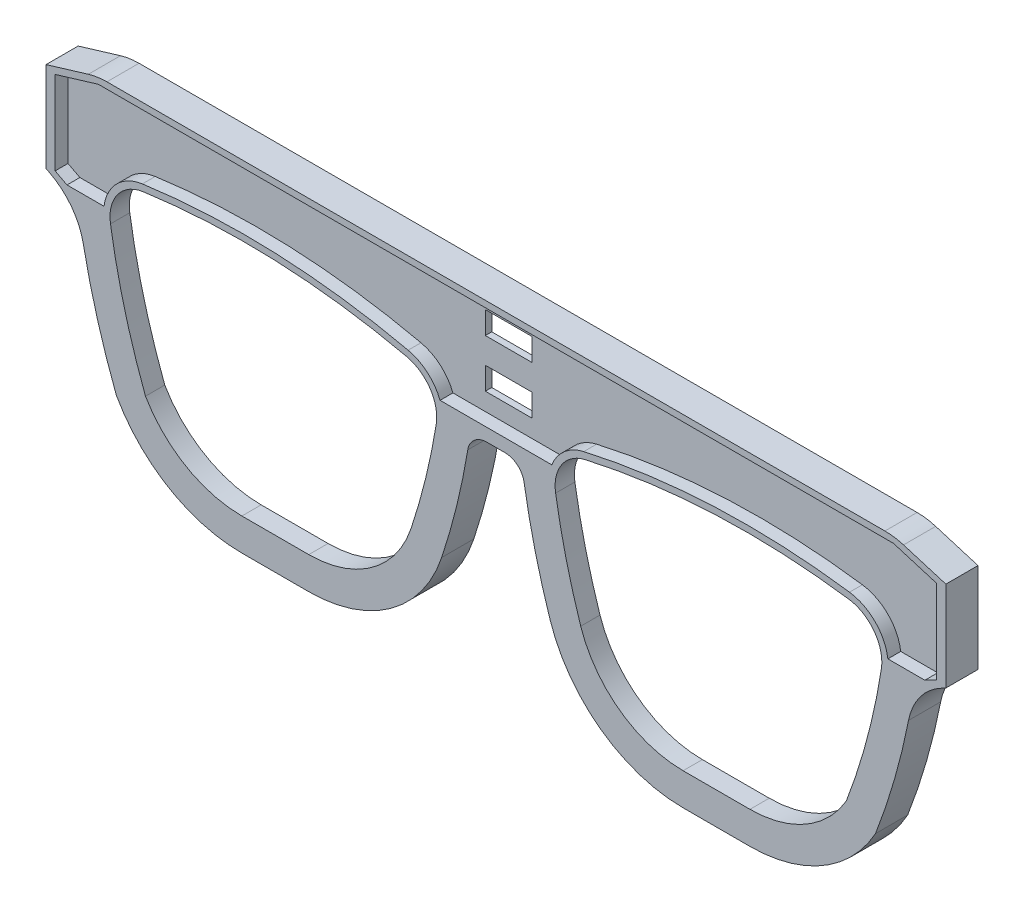
SolidWorks part; units mm, degrees
ref_plane "Front Plane" through (0, 0, 0) normal (0, 0, 1) x (1, 0, 0)
ref_plane "Top Plane" through (0, 0, 0) normal (0, 1, 0) x (1, 0, 0)
ref_plane "Right Plane" through (0, 0, 0) normal (1, 0, 0) x (0, 0, -1)
sketch "Sketch1" plane through (0, 0, 0) normal (0, 0, 1) x (1, 0, 0)
  line L4 (-70, 16.5826) -> (-70, 2.5826)
  line L5 (-70, 2.5826) -> (-65, -0.0353)
  line L6 (-39.5244, -34) -> (-29.1194, -34)
  line L7 (-4, 0) -> (0, 0)
  line L8 (0, 45.3197) -> (0, -37.9766) construction
  line L11 (-62, 19) -> (0, 19)
  line L12 (0, 19) -> (0, 0)
  line L13 (-70, 16.5826) -> (-62, 19)
  arc A2 (-8.4439, -19.0581) -> (-4, 0) centre (-111.6609, 15.057) ccw
  arc A3 (-65, -0.0353) -> (-59.0574, -22.499) centre (40.965, 15.9791) ccw
  arc A4 (-59.0574, -22.499) -> (-39.5244, -34) centre (-39.5244, -11.6623) ccw
  arc A5 (-29.1194, -34) -> (-8.4439, -19.0581) centre (-29.1194, -12.2244) ccw
  dimension "D8" = 5
  dimension "D1" = 4
  dimension "D2" = 53
  dimension "D3" = 34
  dimension "D4" = 70
  dimension "D5" = 8
  dimension "D7" = 14
extrude "Boss-Extrude1" add sketch "Sketch1" along normal blind 5 contours L4 L5 A3 A4 L6 A5 A2 L7 L12 L11 L13
sketch "Sketch2" plane through (0, 0, 5) normal (0, 0, 1) x (1, 0, 0)
  line L7 (-39.5244, -29) -> (-29.1194, -29)
  line L8 (-39.5244, -29) -> (-29.1194, -29)
  arc A15 (-60.0561, 0.7118) -> (-59.2887, 6.3037) centre (-50.178, 2.2047) cw
  arc A16 (-59.2887, 6.3037) -> (-8.9375, 4.059) centre (-39.064, -105.8745) cw
  arc A17 (-8.9375, 4.059) -> (-8.9518, 0.6925) centre (-21.3647, 2.4286) cw
  arc A19 (-13.1913, -17.489) -> (-8.9518, 0.6925) centre (-111.6609, 15.057) ccw
  arc A20 (-29.1194, -29) -> (-13.1913, -17.489) centre (-29.1194, -12.2244) ccw
  arc A21 (-54.5219, -20.3612) -> (-39.5244, -29) centre (-39.5244, -11.6623) ccw
  arc A22 (-60.0561, 0.7118) -> (-54.5219, -20.3612) centre (40.965, 15.9791) ccw
  arc A23 (-13.1913, -17.489) -> (-8.9518, 0.6925) centre (-111.6609, 15.057) ccw
  arc A24 (-29.1194, -29) -> (-13.1913, -17.489) centre (-29.1194, -12.2244) ccw
  arc A25 (-54.5219, -20.3612) -> (-39.5244, -29) centre (-39.5244, -11.6623) ccw
  arc A26 (-60.0561, 0.7118) -> (-54.5219, -20.3612) centre (40.965, 15.9791) ccw
  dimension "D1" = 5
extrude "Cut-Extrude1" cut sketch "Sketch2" against normal through all
fillet "Fillet1" radius 6 2 edges at (-8.9375, 4.059, 2.5) (-59.2887, 6.3037, 2.5)
sketch "Sketch3" plane through (0, 0, 5) normal (0, 0, 1) x (1, 0, 0)
  line L0 (-68.579, 15.9673) -> (-61.8522, 18)
  line L1 (-70, 16.5826) -> (-62, 19) construction
  line L3 (-61.8522, 18) -> (61.8522, 18)
  line L4 (0, 2) -> (0, 18)
  line L7 (-68.579, 15.9673) -> (-68.579, 2.9673)
  line L8 (-66.7315, 2) -> (-60.9781, 2)
  line L12 (-4.3821, 2) -> (4.3821, 2)
  line L13 (-4, 0) -> (0, 0) construction
  line L14 (-68.579, 2.9673) -> (-66.7315, 2)
  line L15 (-70, 2.5826) -> (-65, -0.0353) construction
  line L16 (-4.3821, 2) -> (-8.6909, 2)
  line L18 (68.579, 15.9673) -> (61.8522, 18)
  line L19 (4.3821, 2) -> (8.6909, 2)
  line L20 (68.579, 2.9673) -> (66.7315, 2)
  line L22 (66.7315, 2) -> (60.9781, 2)
  line L23 (68.579, 15.9673) -> (68.579, 2.9673)
  arc A0 (13.6612, 6.2712) -> (55.0112, 8.0011) centre (39.064, -105.8745) cw
  arc A1 (-13.8821, 5.2959) -> (-54.8725, 7.0107) centre (-39.064, -105.8745) ccw construction
  arc A2 (55.0112, 8.0011) -> (60.9781, 2) centre (54.0404, 1.0687) cw
  arc A3 (8.6909, 2) -> (13.6612, 6.2712) centre (15.2077, -0.5559) cw
  arc A10 (-8.2976, -1.6744) -> (-13.6612, 6.2712) centre (-15.2077, -0.5559) ccw
  arc A11 (-55.0112, 8.0011) -> (-60.9557, -0.0166) centre (-54.0404, 1.0687) ccw
  arc A12 (-13.6612, 6.2712) -> (-55.0112, 8.0011) centre (-39.064, -105.8745) ccw
  arc A13 (-8.6909, 2) -> (-13.6612, 6.2712) centre (-15.2077, -0.5559) ccw
  arc A14 (-55.0112, 8.0011) -> (-60.9781, 2) centre (-54.0404, 1.0687) ccw
  arc A15 (-13.6612, 6.2712) -> (-55.0112, 8.0011) centre (-39.064, -105.8745) ccw
  point P26 (39.064, 8.1123)
  point P40 (-39.064, 8.1123)
  line M33 (0, 0) -> (0, 19)
  dimension "D2" = 2
  dimension "D1" = 1
  dimension "D4" = 1
  dimension "D5" = 1
fillet "Fillet4" radius 3 1 edges at (-4, 0, 2.5)
fillet "Fillet5" radius 10 2 edges at (-65, -0.0353, 2.5) (-62, 19, 2.5)
mirror "Mirror2" about plane through (0, 19, 5) normal (1, 0, 0) of "Fillet5", "Fillet4", "Boss-Extrude1", "Cut-Extrude1", "Fillet1"
extrude "Cut-Extrude2" cut sketch "Sketch3" against normal blind 2 contours A15 A13 L16 L12 L3 L0 L7 L14 L8 A14 M33 | L19 A3 A0 A2 L22 L20 L23 L18 L3 L12 M33
sketch "Sketch4" plane through (0, 0, 3) normal (0, 0, 1) x (1, 0, 0)
  line L1 (3.65, 15.75) -> (-3.65, 15.75)
  line L2 (3.65, 15.75) -> (3.65, 12.25)
  line L3 (3.65, 12.25) -> (-3.65, 12.25)
  line L4 (-3.65, 15.75) -> (-3.65, 12.25)
  line L5 (3.65, 15.75) -> (-3.65, 12.25) construction
  line L6 (3.65, 12.25) -> (-3.65, 15.75) construction
  line L7 (3.65, 8.25) -> (-3.65, 8.25)
  line L8 (3.65, 8.25) -> (3.65, 4.75)
  line L9 (3.65, 4.75) -> (-3.65, 4.75)
  line L10 (-3.65, 8.25) -> (-3.65, 4.75)
  line L11 (3.65, 8.25) -> (-3.65, 4.75) construction
  line L12 (3.65, 4.75) -> (-3.65, 8.25) construction
  point P0 (0, 14)
  point P5 (0, 6.5)
  dimension "D1" = 3.5
  dimension "D2" = 7.3
  dimension "D3" = 6.5
  dimension "D4" = 14
extrude "Cut-Extrude3" cut sketch "Sketch4" against normal through all
sketch "Sketch5" plane through (0, 19, 0) normal (0, 1, 0) x (1, 0, 0)
  line L0 (-60.5221, 0) -> (60.5221, 0) construction
  line L1 (7, -5) -> (-7, -5) construction
  line L2 (7, -5) -> (7, 0) construction
  line L3 (7, 0) -> (-7, 0) construction
  line L4 (-7, -5) -> (-7, 0) construction
  line L5 (7, -5) -> (-7, 0) construction
  line L6 (7, 0) -> (-7, -5) construction
  line L7 (-60.5221, -5) -> (60.5221, -5) construction
  point P0 (0, -2.5)
  dimension "D1" = 14
sketch "Sketch6" plane through (0, 0, 3) normal (0, 0, 1) x (1, 0, 0)
  line L27 (69, 15.8401) -> (63.1254, 17.6153)
  line L28 (60.5221, 18) -> (-60.5221, 18)
  line L29 (-63.1254, 17.6153) -> (-69, 15.8401)
  line L40 (-69, 15.8401) -> (-69, 3.1878)
  line L41 (-69, 3.1878) -> (-68.9032, 3.1371)
  line L42 (-39.5244, -33) -> (-29.1194, -33)
  line L43 (-1.4213, 1) -> (1.4213, 1)
  line L44 (29.1194, -33) -> (39.5244, -33)
  line L45 (68.9032, 3.1371) -> (69, 3.1878)
  line L46 (69, 3.1878) -> (69, 15.8401)
  line L47 (69, 15.8401) -> (63.1254, 17.6153)
  line L48 (60.5221, 18) -> (-60.5221, 18)
  line L49 (-63.1254, 17.6153) -> (-69, 15.8401)
  line L50 (-69, 15.8401) -> (-69, 3.1878)
  line L51 (-69, 3.1878) -> (-68.9032, 3.1371)
  line L52 (-39.5244, -33) -> (-29.1194, -33)
  line L53 (-1.4213, 1) -> (1.4213, 1)
  line L54 (29.1194, -33) -> (39.5244, -33)
  line L55 (68.9032, 3.1371) -> (69, 3.1878)
  line L56 (69, 3.1878) -> (69, 15.8401)
  line L57 (39.5244, -29) -> (29.1194, -29) construction
  line L60 (-39.5244, -29) -> (-29.1194, -29) construction
  line L61 (39.5244, -29) -> (29.1194, -29)
  line L62 (-39.5244, -29) -> (-29.1194, -29)
  arc A73 (63.1254, 17.6153) -> (60.5221, 18) centre (60.5221, 9) ccw
  arc A74 (-60.5221, 18) -> (-63.1254, 17.6153) centre (-60.5221, 9) ccw
  arc A75 (-63.2119, -4.4874) -> (-68.9032, 3.1371) centre (-74.0056, -6.6079) ccw
  arc A76 (-63.2119, -4.4874) -> (-58.1493, -22.0743) centre (40.965, 15.9791) ccw
  arc A77 (-58.1493, -22.0743) -> (-39.5244, -33) centre (-39.5244, -11.6623) ccw
  arc A78 (-29.1194, -33) -> (-9.3934, -18.7443) centre (-29.1194, -12.2244) ccw
  arc A79 (-9.3934, -18.7443) -> (-5.3687, -2.3534) centre (-111.6609, 15.057) ccw
  arc A80 (-1.4213, 1) -> (-5.3687, -2.3534) centre (-1.4213, -3) ccw
  arc A81 (5.3687, -2.3534) -> (1.4213, 1) centre (1.4213, -3) ccw
  arc A82 (5.3687, -2.3534) -> (9.3934, -18.7443) centre (111.6609, 15.057) ccw
  arc A83 (9.3934, -18.7443) -> (29.1194, -33) centre (29.1194, -12.2244) ccw
  arc A84 (39.5244, -33) -> (58.1493, -22.0743) centre (39.5244, -11.6623) ccw
  arc A85 (58.1493, -22.0743) -> (63.2119, -4.4874) centre (-40.965, 15.9791) ccw
  arc A86 (68.9032, 3.1371) -> (63.2119, -4.4874) centre (74.0056, -6.6079) ccw
  arc A87 (63.1254, 17.6153) -> (60.5221, 18) centre (60.5221, 9) ccw
  arc A88 (-60.5221, 18) -> (-63.1254, 17.6153) centre (-60.5221, 9) ccw
  arc A89 (-63.2119, -4.4874) -> (-68.9032, 3.1371) centre (-74.0056, -6.6079) ccw
  arc A90 (-63.2119, -4.4874) -> (-58.1493, -22.0743) centre (40.965, 15.9791) ccw
  arc A91 (-58.1493, -22.0743) -> (-39.5244, -33) centre (-39.5244, -11.6623) ccw
  arc A92 (-29.1194, -33) -> (-9.3934, -18.7443) centre (-29.1194, -12.2244) ccw
  arc A93 (-9.3934, -18.7443) -> (-5.3687, -2.3534) centre (-111.6609, 15.057) ccw
  arc A94 (-1.4213, 1) -> (-5.3687, -2.3534) centre (-1.4213, -3) ccw
  arc A95 (5.3687, -2.3534) -> (1.4213, 1) centre (1.4213, -3) ccw
  arc A96 (5.3687, -2.3534) -> (9.3934, -18.7443) centre (111.6609, 15.057) ccw
  arc A97 (9.3934, -18.7443) -> (29.1194, -33) centre (29.1194, -12.2244) ccw
  arc A98 (39.5244, -33) -> (58.1493, -22.0743) centre (39.5244, -11.6623) ccw
  arc A99 (58.1493, -22.0743) -> (63.2119, -4.4874) centre (-40.965, 15.9791) ccw
  arc A100 (68.9032, 3.1371) -> (63.2119, -4.4874) centre (74.0056, -6.6079) ccw
  arc A182 (9.2847, -1.5146) -> (13.1913, -17.489) centre (111.6609, 15.057) ccw construction
  arc A183 (13.1913, -17.489) -> (29.1194, -29) centre (29.1194, -12.2244) ccw construction
  arc A184 (39.5244, -29) -> (54.5219, -20.3612) centre (39.5244, -11.6623) ccw construction
  arc A185 (54.5219, -20.3612) -> (59.9678, 0.1384) centre (-40.965, 15.9791) ccw construction
  arc A186 (59.9678, 0.1384) -> (54.8725, 7.0107) centre (54.0404, 1.0687) ccw construction
  arc A187 (54.8725, 7.0107) -> (13.8821, 5.2959) centre (39.064, -105.8745) ccw construction
  arc A188 (13.8821, 5.2959) -> (9.2847, -1.5146) centre (15.2077, -0.5559) ccw construction
  arc A194 (-9.2847, -1.5146) -> (-13.8821, 5.2959) centre (-15.2077, -0.5559) ccw construction
  arc A203 (-13.1913, -17.489) -> (-9.2847, -1.5146) centre (-111.6609, 15.057) ccw construction
  arc A204 (-29.1194, -29) -> (-13.1913, -17.489) centre (-29.1194, -12.2244) ccw construction
  arc A205 (-54.5219, -20.3612) -> (-39.5244, -29) centre (-39.5244, -11.6623) ccw construction
  arc A206 (-59.9678, 0.1384) -> (-54.5219, -20.3612) centre (40.965, 15.9791) ccw construction
  arc A207 (-54.8725, 7.0107) -> (-59.9678, 0.1384) centre (-54.0404, 1.0687) ccw construction
  arc A208 (-13.8821, 5.2959) -> (-54.8725, 7.0107) centre (-39.064, -105.8745) ccw construction
  arc A209 (9.2847, -1.5146) -> (13.1913, -17.489) centre (111.6609, 15.057) ccw
  arc A210 (13.1913, -17.489) -> (29.1194, -29) centre (29.1194, -12.2244) ccw
  arc A211 (39.5244, -29) -> (54.5219, -20.3612) centre (39.5244, -11.6623) ccw
  arc A212 (54.5219, -20.3612) -> (59.9678, 0.1384) centre (-40.965, 15.9791) ccw
  arc A213 (59.9678, 0.1384) -> (54.8725, 7.0107) centre (54.0404, 1.0687) ccw
  arc A214 (54.8725, 7.0107) -> (13.8821, 5.2959) centre (39.064, -105.8745) ccw
  arc A215 (13.8821, 5.2959) -> (9.2847, -1.5146) centre (15.2077, -0.5559) ccw
  arc A216 (-9.2847, -1.5146) -> (-13.8821, 5.2959) centre (-15.2077, -0.5559) ccw
  arc A217 (-13.1913, -17.489) -> (-9.2847, -1.5146) centre (-111.6609, 15.057) ccw
  arc A218 (-29.1194, -29) -> (-13.1913, -17.489) centre (-29.1194, -12.2244) ccw
  arc A219 (-54.5219, -20.3612) -> (-39.5244, -29) centre (-39.5244, -11.6623) ccw
  arc A220 (-59.9678, 0.1384) -> (-54.5219, -20.3612) centre (40.965, 15.9791) ccw
  arc A221 (-54.8725, 7.0107) -> (-59.9678, 0.1384) centre (-54.0404, 1.0687) ccw
  arc A222 (-13.8821, 5.2959) -> (-54.8725, 7.0107) centre (-39.064, -105.8745) ccw
  dimension "D1" = 1
extrude "Cut-Extrude4" cut sketch "Sketch6" along normal blind 2 from surface at -3 starting at face at (0, 14, 0)
